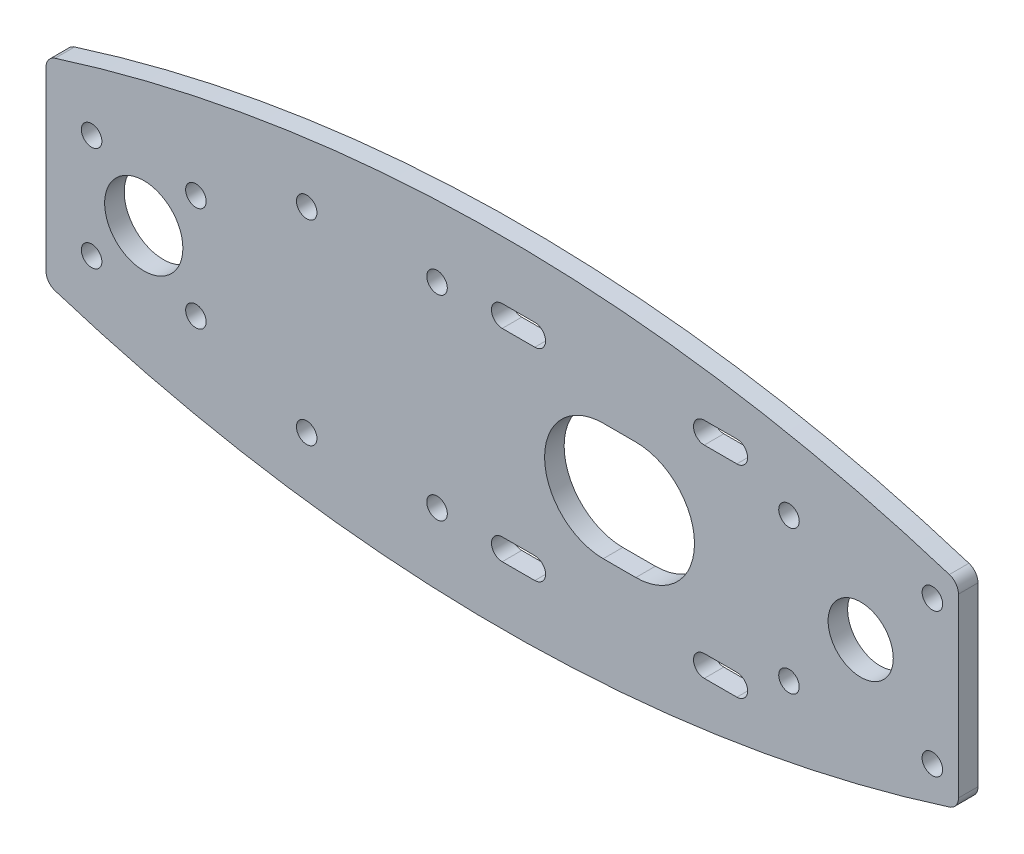
SolidWorks part; units mm, degrees
ref_plane "前视基准面" through (0, 0, 0) normal (0, 0, 1) x (1, 0, 0)
ref_plane "上视基准面" through (0, 0, 0) normal (0, 1, 0) x (1, 0, 0)
ref_plane "右视基准面" through (0, 0, 0) normal (1, 0, 0) x (0, 0, -1)
sketch "Model" plane through (0, 0, 0) normal (0, 0, 1) x (1, 0, 0)
  line L64 (0, -19.107) -> (0, 16.0901) construction
  line L65 (-23.531, 0) -> (19.7113, 0) construction
  line L66 (-73, 16.0901) -> (-73, -13.5761) construction
  line L67 (-84.8746, 0) -> (-60.7394, 0) construction
  line L68 (-88, 13.5429) -> (-88, -13.5429)
  line L69 (52, -13.5429) -> (52, 13.5429)
  line L70 (2.5, 9) -> (-2.5, 9)
  line L71 (-2.5, -9) -> (2.5, -9)
  line L72 (-13, 17.15) -> (-18, 17.15)
  line L73 (-18, 13.85) -> (-13, 13.85)
  line L74 (18, 17.15) -> (13, 17.15)
  line L75 (13, 13.85) -> (18, 13.85)
  line L76 (13, -17.15) -> (18, -17.15)
  line L77 (18, -13.85) -> (13, -13.85)
  line L78 (-13, -13.85) -> (-18, -13.85)
  line L79 (-18, -17.15) -> (-13, -17.15)
  circle A0 centre (37, 0) radius 5
  arc A1 (50.6068, -15.4486) -> (52, -13.5429) centre (50, -13.5429) ccw
  arc A2 (-86.6068, -15.4486) -> (50.6068, -15.4486) centre (-18, 200) ccw
  arc A3 (-88, -13.5429) -> (-86.6068, -15.4486) centre (-86, -13.5429) ccw
  arc A4 (-86.6068, 15.4486) -> (-88, 13.5429) centre (-86, 13.5429) ccw
  arc A5 (50.6068, 15.4486) -> (-86.6068, 15.4486) centre (-18, -200) ccw
  arc A6 (52, 13.5429) -> (50.6068, 15.4486) centre (50, 13.5429) ccw
  circle A7 centre (-73, 0) radius 6
  arc A8 (2.5, -9) -> (2.5, 9) centre (2.5, 0) ccw
  arc A9 (-2.5, 9) -> (-2.5, -9) centre (-2.5, 0) ccw
  arc A10 (-13, 13.85) -> (-13, 17.15) centre (-13, 15.5) ccw
  arc A11 (-18, 17.15) -> (-18, 13.85) centre (-18, 15.5) ccw
  arc A12 (18, 13.85) -> (18, 17.15) centre (18, 15.5) ccw
  arc A13 (13, 17.15) -> (13, 13.85) centre (13, 15.5) ccw
  arc A14 (13, -13.85) -> (13, -17.15) centre (13, -15.5) ccw
  arc A15 (18, -17.15) -> (18, -13.85) centre (18, -15.5) ccw
  arc A16 (-13, -17.15) -> (-13, -13.85) centre (-13, -15.5) ccw
  arc A17 (-18, -13.85) -> (-18, -17.15) centre (-18, -15.5) ccw
  circle A18 centre (26, 11) radius 1.575
  circle A19 centre (48, 11) radius 1.575
  circle A20 centre (48, -11) radius 1.575
  circle A21 centre (26, -11) radius 1.575
  circle A22 centre (-81, 8) radius 1.575
  circle A23 centre (-65, 8) radius 1.575
  circle A24 centre (-65, -8) radius 1.575
  circle A25 centre (-81, -8) radius 1.575
  circle A26 centre (-28, 15) radius 1.575
  circle A27 centre (-28, -15) radius 1.575
  circle A28 centre (-48, -15) radius 1.575
  circle A29 centre (-48, 15) radius 1.575
extrude "凸台-拉伸1" add sketch "Model" along normal blind 3
